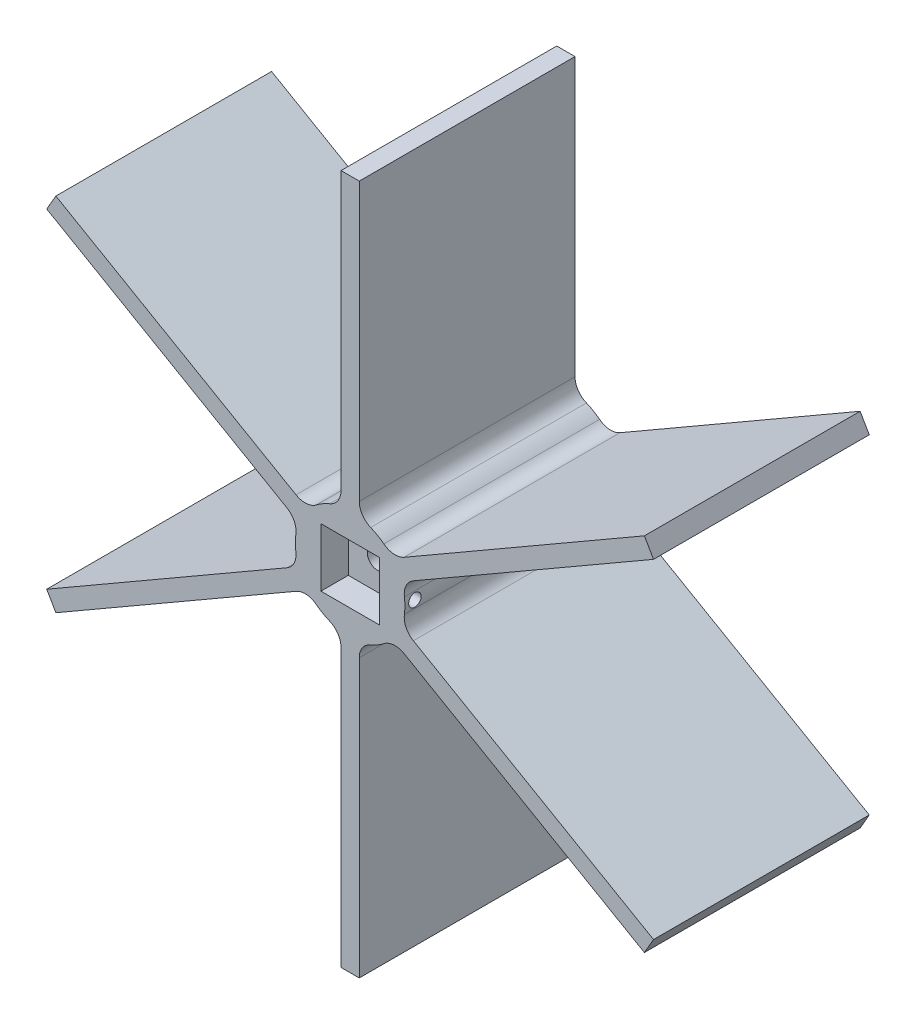
SolidWorks part; units mm, degrees
ref_plane "Front Plane" through (0, 0, 0) normal (0, 0, 1) x (1, 0, 0)
ref_plane "Top Plane" through (0, 0, 0) normal (0, 1, 0) x (1, 0, 0)
ref_plane "Right Plane" through (0, 0, 0) normal (1, 0, 0) x (0, 0, -1)
sketch "Sketch1" plane through (0, 0, 0) normal (0, 0, 1) x (1, 0, 0)
  line L0 (-3.175, 0) -> (3.175, 0)
  line L2 (-3.175, 0) -> (-3.175, 119.958)
  line L3 (-3.175, 119.958) -> (3.175, 119.958)
  line L4 (3.175, 0) -> (3.175, 119.958)
  line L5 (-3.175, -119.958) -> (3.175, 119.958) construction
  line L6 (-3.175, 119.958) -> (3.175, -119.958) construction
  circle A0 centre (0, 0) radius 120
  circle A1 centre (0, 0) radius 19.05
  dimension "D1" = 240
  dimension "D3" = 38.1
  dimension "D2" = 6.35
extrude "Boss-Extrude1" add sketch "Sketch1" along normal mid plane 75 contours A1 L4 L3 L2 | L2 A1 L4 L0 | L4 A1 L2 L0
pattern_circular "CirPattern1" count 6 over 360 about axis through (0, 0, 0) along (0, 0, 1) of "Boss-Extrude1"
fillet "Fillet1" radius 6.35 12 edges at (14.6795, 12.1414, 0) (3.175, 18.7836, 0) (-3.175, 18.7836, 0) (-14.6795, 12.1414, 0) (-17.8545, 6.6421, 0) (-17.8545, -6.6421, 0) (-14.6795, -12.1414, 0) (-3.175, -18.7836, 0) (3.175, -18.7836, 0) (14.6795, -12.1414, 0) (17.8545, -6.6421, 0) (17.8545, 6.6421, 0)
sketch "Sketch2" plane through (0, 0, 37.5) normal (0, 0, 1) x (1, 0, 0)
  line L1 (-10.16, 10.16) -> (10.16, 10.16)
  line L2 (-10.16, 10.16) -> (-10.16, -10.16)
  line L3 (-10.16, -10.16) -> (10.16, -10.16)
  line L4 (10.16, 10.16) -> (10.16, -10.16)
  line L5 (-10.16, 10.16) -> (10.16, -10.16) construction
  line L6 (-10.16, -10.16) -> (10.16, 10.16) construction
  point P0 (0, 0)
  dimension "D1" = 20.32
  dimension "D2" = 20.32
extrude "Cut-Extrude1" cut sketch "Sketch2" against normal blind 9.525
sketch "Sketch3" plane through (0, 0, 27.975) normal (0, 0, 1) x (1, 0, 0)
  circle A0 centre (0, 0) radius 3.5719
  dimension "D1" = 7.1437
extrude "Cut-Extrude2" cut sketch "Sketch3" against normal through all
sketch "Sketch4" plane through (10.16, 0, 0) normal (-1, 0, 0) x (0, 0, 1)
  line L0 (37.5, -10.16) -> (37.5, 10.16) construction
  circle A0 centre (34.0075, 0) radius 2.1828
  point P5 (37.5, 0)
  dimension "D1" = 4.3656
  dimension "D2" = 3.4925
extrude "Cut-Extrude3" cut sketch "Sketch4" against normal through all contours A0
